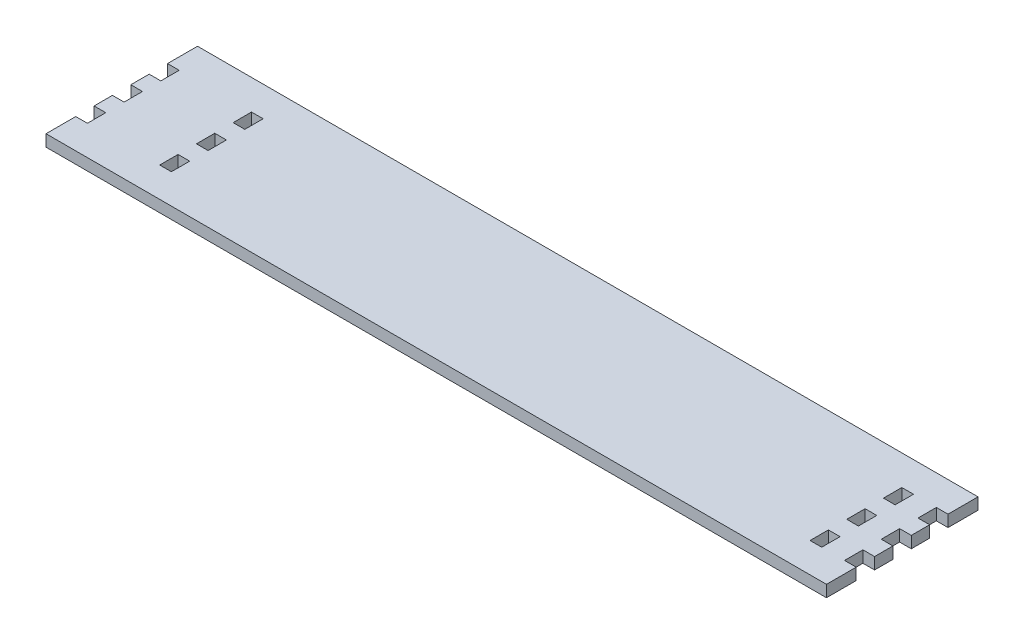
SolidWorks part; units mm, degrees
ref_plane "Front Plane" through (0, 0, 0) normal (0, 0, 1) x (1, 0, 0)
ref_plane "Top Plane" through (0, 0, 0) normal (0, 1, 0) x (1, 0, 0)
ref_plane "Right Plane" through (0, 0, 0) normal (1, 0, 0) x (0, 0, -1)
sketch "Sketch1" plane through (0, 0, 0) normal (0, 1, 0) x (1, 0, 0)
  line L0 (-212.598, -5) -> (-209.423, -5)
  line L1 (-3.175, 0) -> (-209.423, 0) construction
  line L2 (-186.549, -5) -> (-186.549, 0) construction
  line L3 (-3.175, -38.1) -> (-209.423, -38.1)
  line L4 (-212.598, -30) -> (-212.598, -38.1)
  line L5 (-3.175, -25) -> (-3.175, -30)
  line L6 (-212.598, -5) -> (-212.598, 0)
  line L7 (-212.598, 0) -> (-209.423, 0) construction
  line L8 (-212.598, -10) -> (-209.423, -10)
  line L9 (-3.175, -15) -> (-3.175, -20)
  line L10 (-3.175, -5) -> (-3.175, -10)
  line L11 (-209.423, -15) -> (-212.598, -15)
  line L12 (0, -20) -> (0, -25)
  line L13 (-212.598, -20) -> (-209.423, -20)
  line L14 (0, -10) -> (0, -15)
  line L15 (-209.423, -25) -> (-212.598, -25)
  line L16 (-212.598, -38.1) -> (-209.423, -38.1)
  line L17 (-212.598, -30) -> (-209.423, -30)
  line L18 (0, -30) -> (-3.175, -30)
  line L19 (-189.724, -5) -> (-186.549, -5)
  line L20 (0, -38.1) -> (-3.175, -38.1)
  line L21 (-106.299, 0) -> (-106.299, -38.1) construction
  line L22 (-3.175, 0) -> (0, 0) construction
  line L23 (0, 0) -> (0, -5) construction
  line L24 (-212.598, -10) -> (-212.598, -15)
  line L25 (-212.598, -20) -> (-212.598, -25)
  line L26 (-189.724, -5) -> (-189.724, -10)
  line L27 (-189.724, -10) -> (-186.549, -10)
  line L28 (0, -30) -> (-3.175, -30)
  line L29 (-3.175, -25) -> (0, -25)
  line L30 (-186.549, -5) -> (-186.549, -10)
  line L31 (0, -20) -> (-3.175, -20)
  line L32 (-189.724, -15) -> (-186.549, -15)
  line L33 (-3.175, -15) -> (0, -15)
  line L34 (-189.724, -15) -> (-189.724, -20)
  line L35 (-189.724, -20) -> (-186.549, -20)
  line L36 (0, -10) -> (-3.175, -10)
  line L37 (-186.549, -15) -> (-186.549, -20)
  line L38 (0, -5) -> (-3.175, -5)
  line L39 (-209.423, -5) -> (-209.423, -10)
  line L40 (-209.423, -15) -> (-209.423, -20)
  line L41 (-209.423, -25) -> (-209.423, -30)
  line L42 (-3.175, -25) -> (0, -25)
  line L43 (0, -20) -> (-3.175, -20)
  line L44 (-3.175, -15) -> (0, -15)
  line L45 (0, -10) -> (-3.175, -10)
  line L46 (0, 0) -> (-3.175, 0) construction
  line L47 (0, -5) -> (0, 0)
  line L48 (0, -30) -> (0, -38.1)
  line L49 (0, -5) -> (-3.175, -5)
  line L50 (-189.724, -25) -> (-186.549, -25)
  line L51 (-189.724, -25) -> (-189.724, -30)
  line L52 (-189.724, -30) -> (-186.549, -30)
  line L53 (-186.549, -25) -> (-186.549, -30)
  line L54 (-186.549, -10) -> (-186.549, -15) construction
  line L55 (-186.549, -20) -> (-186.549, -25) construction
  line L56 (-12.573, -20) -> (-12.573, -25) construction
  line L57 (-12.573, -10) -> (-12.573, -15) construction
  line L58 (-12.573, -5) -> (-12.573, 0) construction
  line L59 (-12.573, -25) -> (-12.573, -30)
  line L60 (-9.398, -30) -> (-12.573, -30)
  line L61 (-9.398, -25) -> (-9.398, -30)
  line L62 (-9.398, -25) -> (-12.573, -25)
  line L63 (-12.573, -15) -> (-12.573, -20)
  line L64 (-9.398, -20) -> (-12.573, -20)
  line L65 (-9.398, -15) -> (-9.398, -20)
  line L66 (-9.398, -15) -> (-12.573, -15)
  line L67 (-12.573, -5) -> (-12.573, -10)
  line L68 (-9.398, -10) -> (-12.573, -10)
  line L69 (-9.398, -5) -> (-9.398, -10)
  line L70 (-9.398, -5) -> (-12.573, -5)
  line L71 (-212.598, 0) -> (-212.598, 3.175)
  line L72 (-212.598, 3.175) -> (0, 3.175)
  line L73 (0, 3.175) -> (0, 0)
  dimension "D1" = 5
  dimension "D2" = 212.598
  dimension "D3" = 3.175
  dimension "D4" = 5
  dimension "D5" = 38.1
  dimension "D6" = 5
  dimension "D7" = 5
  dimension "D8" = 3.175
  dimension "D9" = 19.699
  dimension "D10" = 3.175
extrude "Boss-Extrude1" add sketch "Sketch1" along normal blind 3.175 contours L48 L18 L5 L29 L12 L31 L9 L33 L14 L36 L10 L38 L47 L46 L1 L7 L6 L0 L39 L8 L24 L11 L40 L13 L25 L15 L41 L17 L4 L16 L3 L20
